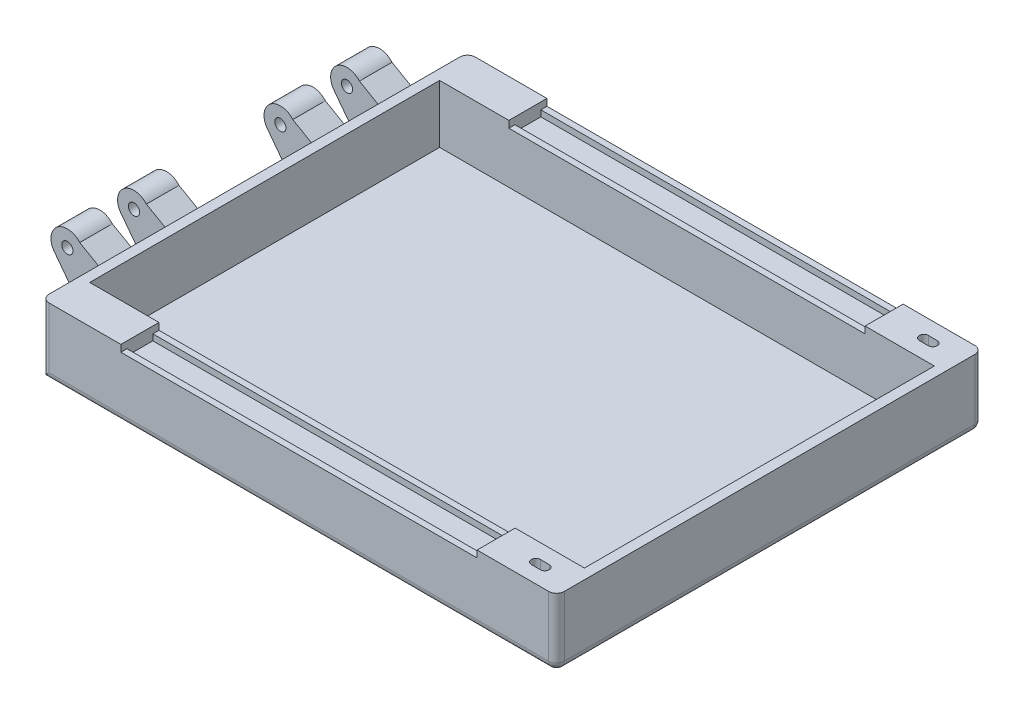
SolidWorks part; units mm, degrees
ref_plane "Front Plane" through (0, 0, 0) normal (0, 0, 1) x (1, 0, 0)
ref_plane "Top Plane" through (0, 0, 0) normal (0, 1, 0) x (1, 0, 0)
ref_plane "Right Plane" through (0, 0, 0) normal (1, 0, 0) x (0, 0, -1)
sketch "Sketch1" plane through (0, 0, 0) normal (0, 1, 0) x (1, 0, 0)
  line L1 (-126.52, -104.66) -> (126.52, -104.66)
  line L2 (-126.52, -104.66) -> (-126.52, 104.66)
  line L3 (-126.52, 104.66) -> (126.52, 104.66)
  line L4 (126.52, -104.66) -> (126.52, 104.66)
  line L5 (-126.52, -104.66) -> (126.52, 104.66) construction
  line L6 (-126.52, 104.66) -> (126.52, -104.66) construction
  point P0 (0, 0)
  dimension "D1" = 253.04
  dimension "D2" = 209.32
extrude "Boss-Extrude1" add sketch "Sketch1" along normal blind 33.5
sketch "Sketch2" plane through (0, 33.5, 0) normal (0, 1, 0) x (1, 0, 0)
  line L1 (-121.52, -85.96) -> (121.52, -85.96)
  line L2 (-121.52, -85.96) -> (-121.52, 85.96)
  line L3 (-121.52, 85.96) -> (121.52, 85.96)
  line L4 (121.52, -85.96) -> (121.52, 85.96)
  line L5 (-121.52, -85.96) -> (121.52, 85.96) construction
  line L6 (-121.52, 85.96) -> (121.52, -85.96) construction
  point P0 (0, 0)
  dimension "D1" = 243.04
  dimension "D2" = 171.92
extrude "Cut-Extrude1" cut sketch "Sketch2" against normal blind 28.5
sketch "Sketch4" plane through (0, 33.5, 0) normal (0, 1, 0) x (1, 0, 0)
  line L0 (-121.52, -85.96) -> (121.52, -85.96) construction
  line L1 (-87.5, -85.96) -> (87.5, -85.96)
  line L2 (-87.5, -85.96) -> (-87.5, -104.66)
  line L3 (-87.5, -104.66) -> (87.5, -104.66)
  line L4 (87.5, -85.96) -> (87.5, -104.66)
  line L5 (-126.52, -104.66) -> (126.52, -104.66) construction
  point P4 (0, -85.96)
  dimension "D1" = 175
extrude "Cut-Extrude2" cut sketch "Sketch4" against normal blind 3.35
sketch "Sketch5" plane through (0, 30.15, 0) normal (0, 1, 0) x (1, 0, 0)
  line L1 (-87.5, -88.96) -> (87.5, -88.96)
  line L2 (-87.5, -88.96) -> (-87.5, -101.66)
  line L3 (-87.5, -101.66) -> (87.5, -101.66)
  line L4 (87.5, -88.96) -> (87.5, -101.66)
  line L5 (-87.5, -85.96) -> (-87.5, -104.66) construction
  point P4 (-87.5, -95.31)
  dimension "D1" = 12.7
  dimension "D2" = 175
extrude "Cut-Extrude3" cut sketch "Sketch5" against normal blind 3
sketch "Sketch6" plane through (0, 33.5, 0) normal (0, 1, 0) x (1, 0, 0)
  line L0 (121.52, 85.96) -> (-121.52, 85.96) construction
  line L1 (-87.5, 104.66) -> (87.5, 104.66)
  line L2 (-87.5, 104.66) -> (-87.5, 85.96)
  line L3 (-87.5, 85.96) -> (87.5, 85.96)
  line L4 (87.5, 104.66) -> (87.5, 85.96)
  point P4 (0, 85.96)
  dimension "D1" = 175
  dimension "D2" = 18.7
extrude "Cut-Extrude4" cut sketch "Sketch6" against normal blind 3.35
sketch "Sketch7" plane through (0, 30.15, 0) normal (0, 1, 0) x (1, 0, 0)
  line L0 (-87.5, 104.66) -> (-87.5, 85.96) construction
  line L1 (-87.5, 101.66) -> (87.5, 101.66)
  line L2 (-87.5, 101.66) -> (-87.5, 88.96)
  line L3 (-87.5, 88.96) -> (87.5, 88.96)
  line L4 (87.5, 101.66) -> (87.5, 88.96)
  point P4 (-87.5, 95.31)
  dimension "D1" = 12.7
  dimension "D2" = 175
extrude "Cut-Extrude5" cut sketch "Sketch7" against normal blind 3
ref_plane "Plane1" through (0, 0, -35.96) normal (0, 0, 1) x (1, 0, 0)
sketch "Sketch9" plane through (0, 0, -35.96) normal (0, 0, 1) x (1, 0, 0)
  line L0 (-126.52, 0) -> (-147.8554, 28.2418)
  line L4 (-126.52, 33.5) -> (-126.52, 0)
  line L5 (-126.52, 33.5) -> (-135.6646, 38.7582)
  arc A0 (-135.6646, 38.7582) -> (-147.8554, 28.2418) centre (-141.76, 33.5) ccw
  circle A1 centre (-141.76, 33.5) radius 2.75
  dimension "D2" = 16.1
  dimension "D3" = 5.5
  dimension "D1" = 15.24
extrude "Boss-Extrude2" add sketch "Sketch9" along normal blind 8 and the other way blind 8
ref_plane "Plane2" through (0, 0, -52.33) normal (0, 0, 1) x (1, 0, 0)
mirror "Mirror1" about plane through (0, 0, -52.33) normal (0, 0, 1) of "Boss-Extrude2"
ref_plane "Plane3" through (0, 0, 0) normal (0, 0, 1) x (1, 0, 0)
mirror "Mirror2" about plane through (0, 0, 0) normal (0, 0, 1) of "Mirror1", "Boss-Extrude2"
sketch "Sketch11" plane through (0, 33.5, 0) normal (0, 1, 0) x (1, 0, 0)
  line L0 (126.52, 104.66) -> (87.5, 104.66) construction
  line L1 (87.5, 85.96) -> (87.5, 104.66) construction
  line L4 (107.01, 93.11) -> (111.41, 93.11)
  line L6 (107.01, 97.51) -> (111.41, 97.51)
  arc A0 (107.01, 97.51) -> (107.01, 93.11) centre (107.01, 95.31) ccw
  arc A1 (111.41, 93.11) -> (111.41, 97.51) centre (111.41, 95.31) ccw
  point P1 (110.31, 95.31)
  point P4 (107.01, 104.66)
  point P7 (87.5, 95.31)
  dimension "D1" = 4.4
  dimension "D4" = 4.4
  dimension "D2" = 4.4
extrude "Cut-Extrude6" cut sketch "Sketch11" against normal blind 33.5
mirror "Mirror3" about plane through (0, 0, 0) normal (0, 0, 1) of "Cut-Extrude6"
fillet "Fillet3" radius 3.81 7 edges at (-126.52, 16.75, 104.66) (0, 0, 104.66) (126.52, 16.75, 104.66) (126.52, 0, 0) (126.52, 16.75, -104.66) (0, 0, -104.66) (-126.52, 16.75, -104.66)
